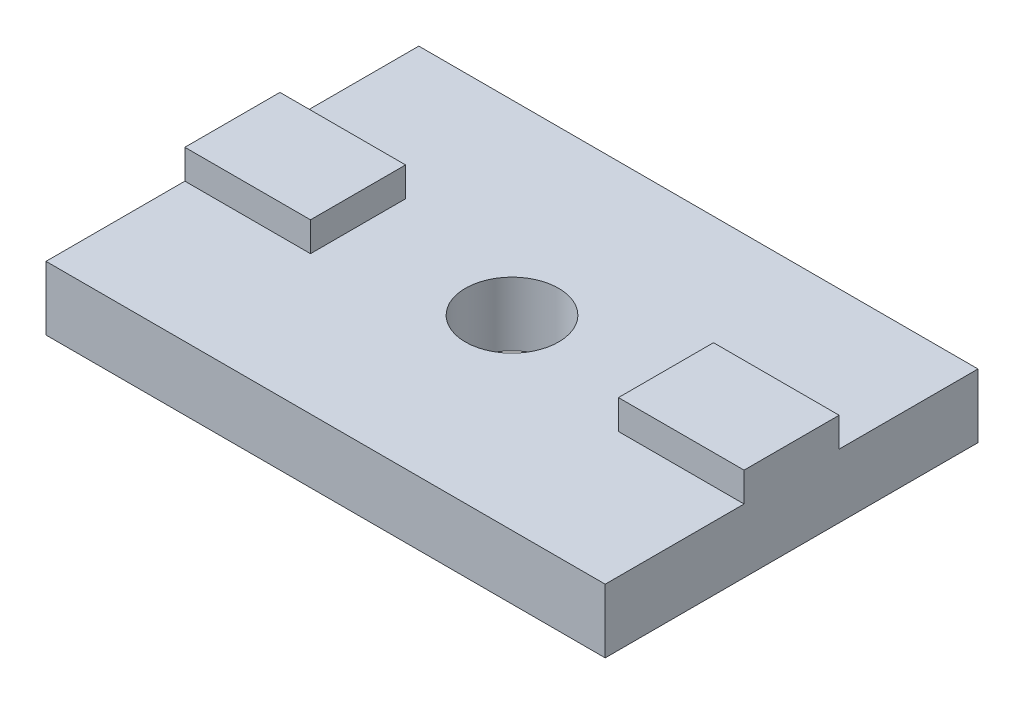
SolidWorks part; units mm, degrees
ref_plane "Front Plane" through (0, 0, 0) normal (0, 0, 1) x (1, 0, 0)
ref_plane "Top Plane" through (0, 0, 0) normal (0, 1, 0) x (1, 0, 0)
ref_plane "Right Plane" through (0, 0, 0) normal (1, 0, 0) x (0, 0, -1)
sketch "Sketch1" plane through (0, 0, 0) normal (0, 1, 0) x (1, 0, 0)
  line L0 (-2.8779, 6.2316) -> (35.2221, 31.6316) construction
  line L1 (-2.8779, 6.2316) -> (35.2221, 6.2316)
  line L2 (-2.8779, 6.2316) -> (-2.8779, 31.6316)
  line L3 (-2.8779, 31.6316) -> (35.2221, 31.6316)
  line L4 (35.2221, 6.2316) -> (35.2221, 31.6316)
  line L5 (35.2221, 31.6316) -> (35.3656, 32.0161) construction
  circle A0 centre (16.1721, 18.9316) radius 3.175
  dimension "D3" = 6.35
  dimension "D1" = 38.1
  dimension "D2" = 25.4
extrude "Boss-Extrude1" add sketch "Sketch1" along normal blind 4.35
sketch "Sketch2" plane through (0, 4.35, 0) normal (0, 1, 0) x (1, 0, 0)
  line L0 (-2.8779, 18.9316) -> (35.2221, 18.9316) construction
  line L1 (-2.8779, 31.6316) -> (-2.8779, 6.2316) construction
  line L2 (35.2221, 6.2316) -> (35.2221, 31.6316) construction
  line L3 (16.1721, 31.6316) -> (16.1721, 6.2316) construction
  line L4 (5.6819, 22.1701) -> (-2.8779, 22.1701)
  line L5 (5.6819, 22.1701) -> (5.6819, 15.6932)
  line L6 (5.6819, 15.6932) -> (-2.8779, 15.6932)
  line L7 (-2.8779, 22.1701) -> (-2.8779, 15.6932)
  line L8 (35.2221, 31.6316) -> (-2.8779, 31.6316) construction
  line L9 (-2.8779, 6.2316) -> (35.2221, 6.2316) construction
  line L10 (26.6623, 22.1701) -> (26.6623, 15.6932)
  line L11 (26.6623, 15.6932) -> (35.2221, 15.6932)
  line L12 (35.2221, 22.1701) -> (35.2221, 15.6932)
  line L13 (26.6623, 22.1701) -> (35.2221, 22.1701)
  line L44 (14.4629, 14.4358) -> (17.8814, 14.4358)
  line L45 (20.1244, 13.5079) -> (23.3518, 10.2864)
  line L46 (22.5885, 8.4414) -> (20.4596, 8.4414)
  line L47 (19.4106, 7.3924) -> (19.4106, 7.2806)
  line L48 (20.4596, 6.2316) -> (21.4892, 6.2316)
  line L49 (22.5052, 6.2316) -> (25.7226, 6.2316)
  line L50 (28.8721, 9.3812) -> (28.8721, 12.5985)
  line L51 (28.8721, 13.6145) -> (28.8721, 14.6442)
  line L52 (27.8231, 15.6932) -> (27.7113, 15.6932)
  line L53 (26.6623, 14.6442) -> (26.6623, 12.5295)
  line L54 (24.9092, 11.8022) -> (21.6131, 15.0908)
  line L55 (20.6806, 17.3384) -> (20.6806, 20.5248)
  line L56 (21.6131, 22.7724) -> (24.9092, 26.061)
  line L57 (26.6623, 25.3337) -> (26.6623, 23.2191)
  line L58 (27.7113, 22.1701) -> (27.8231, 22.1701)
  line L59 (28.8721, 23.2191) -> (28.8721, 24.2487)
  line L60 (28.8721, 25.2647) -> (28.8721, 28.482)
  line L61 (25.7226, 31.6316) -> (22.5052, 31.6316)
  line L62 (21.4892, 31.6316) -> (20.4596, 31.6316)
  line L63 (19.4106, 30.5826) -> (19.4106, 30.4708)
  line L64 (20.4596, 29.4218) -> (22.6489, 29.4218)
  line L65 (23.3792, 27.656) -> (20.0704, 24.3548)
  line L66 (17.8279, 23.4274) -> (14.5163, 23.4274)
  line L67 (12.2738, 24.3548) -> (8.9651, 27.656)
  line L68 (9.6953, 29.4218) -> (11.8846, 29.4218)
  line L69 (12.9336, 30.4708) -> (12.9336, 30.5826)
  line L70 (11.8846, 31.6316) -> (10.855, 31.6316)
  line L71 (9.839, 31.6316) -> (6.6217, 31.6316)
  line L72 (3.4721, 28.482) -> (3.4721, 25.2647)
  line L73 (3.4721, 24.2487) -> (3.4721, 23.2191)
  line L74 (4.5211, 22.1701) -> (4.6329, 22.1701)
  line L75 (5.6819, 23.2191) -> (5.6819, 25.3337)
  line L76 (7.435, 26.061) -> (10.7311, 22.7724)
  line L77 (11.6636, 20.5248) -> (11.6636, 17.3384)
  line L78 (10.7311, 15.0908) -> (7.435, 11.8022)
  line L79 (5.6819, 12.5295) -> (5.6819, 14.6442)
  line L80 (4.6329, 15.6932) -> (4.5211, 15.6932)
  line L81 (3.4721, 14.6442) -> (3.4721, 13.6145)
  line L82 (3.4721, 12.5985) -> (3.4721, 9.3812)
  line L83 (6.6217, 6.2316) -> (9.839, 6.2316)
  line L84 (10.855, 6.2316) -> (11.8846, 6.2316)
  line L85 (12.9336, 7.2806) -> (12.9336, 7.3924)
  line L86 (11.8846, 8.4414) -> (9.7557, 8.4414)
  line L87 (8.9925, 10.2864) -> (12.2198, 13.5079)
  line L88 (14.4629, 14.4358) -> (17.8814, 14.4358) construction
  line L89 (20.1244, 13.5079) -> (23.3518, 10.2864) construction
  line L90 (22.5885, 8.4414) -> (20.4596, 8.4414) construction
  line L91 (19.4106, 7.3924) -> (19.4106, 7.2806) construction
  line L92 (20.4596, 6.2316) -> (21.4892, 6.2316) construction
  line L93 (22.5052, 6.2316) -> (25.7226, 6.2316) construction
  line L94 (28.8721, 9.3812) -> (28.8721, 12.5985) construction
  line L95 (28.8721, 13.6145) -> (28.8721, 14.6442) construction
  line L96 (27.8231, 15.6932) -> (27.7113, 15.6932) construction
  line L97 (26.6623, 14.6442) -> (26.6623, 12.5295) construction
  line L98 (24.9092, 11.8022) -> (21.6131, 15.0908) construction
  line L99 (20.6806, 17.3384) -> (20.6806, 20.5248) construction
  line L100 (21.6131, 22.7724) -> (24.9092, 26.061) construction
  line L101 (26.6623, 25.3337) -> (26.6623, 23.2191) construction
  line L102 (27.7113, 22.1701) -> (27.8231, 22.1701) construction
  line L103 (28.8721, 23.2191) -> (28.8721, 24.2487) construction
  line L104 (28.8721, 25.2647) -> (28.8721, 28.482) construction
  line L105 (25.7226, 31.6316) -> (22.5052, 31.6316) construction
  line L106 (21.4892, 31.6316) -> (20.4596, 31.6316) construction
  line L107 (19.4106, 30.5826) -> (19.4106, 30.4708) construction
  line L108 (20.4596, 29.4218) -> (22.6489, 29.4218) construction
  line L109 (23.3792, 27.656) -> (20.0704, 24.3548) construction
  line L110 (17.8279, 23.4274) -> (14.5163, 23.4274) construction
  line L111 (12.2738, 24.3548) -> (8.9651, 27.656) construction
  line L112 (9.6953, 29.4218) -> (11.8846, 29.4218) construction
  line L113 (12.9336, 30.4708) -> (12.9336, 30.5826) construction
  line L114 (11.8846, 31.6316) -> (10.855, 31.6316) construction
  line L115 (9.839, 31.6316) -> (6.6217, 31.6316) construction
  line L116 (3.4721, 28.482) -> (3.4721, 25.2647) construction
  line L117 (3.4721, 24.2487) -> (3.4721, 23.2191) construction
  line L118 (4.5211, 22.1701) -> (4.6329, 22.1701) construction
  line L119 (5.6819, 23.2191) -> (5.6819, 25.3337) construction
  line L120 (7.435, 26.061) -> (10.7311, 22.7724) construction
  line L121 (11.6636, 20.5248) -> (11.6636, 17.3384) construction
  line L122 (10.7311, 15.0908) -> (7.435, 11.8022) construction
  line L123 (5.6819, 12.5295) -> (5.6819, 14.6442) construction
  line L124 (4.6329, 15.6932) -> (4.5211, 15.6932) construction
  line L125 (3.4721, 14.6442) -> (3.4721, 13.6145) construction
  line L126 (3.4721, 12.5985) -> (3.4721, 9.3812) construction
  line L127 (6.6217, 6.2316) -> (9.839, 6.2316) construction
  line L128 (10.855, 6.2316) -> (11.8846, 6.2316) construction
  line L129 (12.9336, 7.2806) -> (12.9336, 7.3924) construction
  line L130 (11.8846, 8.4414) -> (9.7557, 8.4414) construction
  line L131 (8.9925, 10.2864) -> (12.2198, 13.5079) construction
  arc A52 (20.1244, 13.5079) -> (17.8814, 14.4358) centre (17.8814, 11.2608) ccw
  arc A53 (22.5885, 8.4414) -> (23.3518, 10.2864) centre (22.5885, 9.5218) ccw
  arc A54 (20.4596, 8.4414) -> (19.4106, 7.3924) centre (20.4596, 7.3924) ccw
  arc A55 (19.4106, 7.2806) -> (20.4596, 6.2316) centre (20.4596, 7.2806) ccw
  arc A56 (22.5052, 6.2316) -> (21.4892, 6.2316) centre (21.9972, 6.2316) ccw
  arc A57 (26.7386, 6.2318) -> (25.7226, 6.2316) centre (26.2306, 6.2316) ccw
  arc A58 (26.7386, 6.2318) -> (28.872, 8.3652) centre (26.7639, 8.3398) ccw
  arc A59 (28.8721, 9.3812) -> (28.872, 8.3652) centre (28.8721, 8.8732) ccw
  arc A60 (28.8721, 13.6145) -> (28.8721, 12.5985) centre (28.8721, 13.1065) ccw
  arc A61 (28.8721, 14.6442) -> (27.8231, 15.6932) centre (27.8231, 14.6442) ccw
  arc A62 (27.7113, 15.6932) -> (26.6623, 14.6442) centre (27.7113, 14.6442) ccw
  arc A63 (24.9092, 11.8022) -> (26.6623, 12.5295) centre (25.6349, 12.5295) ccw
  arc A64 (20.6806, 17.3384) -> (21.6131, 15.0908) centre (23.8556, 17.3384) ccw
  arc A65 (21.6131, 22.7724) -> (20.6806, 20.5248) centre (23.8556, 20.5248) ccw
  arc A66 (26.6623, 25.3337) -> (24.9092, 26.061) centre (25.6349, 25.3337) ccw
  arc A67 (26.6623, 23.2191) -> (27.7113, 22.1701) centre (27.7113, 23.2191) ccw
  arc A68 (27.8231, 22.1701) -> (28.8721, 23.2191) centre (27.8231, 23.2191) ccw
  arc A69 (28.8721, 25.2647) -> (28.8721, 24.2487) centre (28.8721, 24.7567) ccw
  arc A70 (28.872, 29.498) -> (28.8721, 28.482) centre (28.8721, 28.99) ccw
  arc A71 (28.872, 29.498) -> (26.7386, 31.6315) centre (26.7639, 29.5234) ccw
  arc A72 (25.7226, 31.6316) -> (26.7386, 31.6315) centre (26.2306, 31.6316) ccw
  arc A73 (21.4892, 31.6316) -> (22.5052, 31.6316) centre (21.9972, 31.6316) ccw
  arc A74 (20.4596, 31.6316) -> (19.4106, 30.5826) centre (20.4596, 30.5826) ccw
  arc A75 (19.4106, 30.4708) -> (20.4596, 29.4218) centre (20.4596, 30.4708) ccw
  arc A76 (23.3792, 27.656) -> (22.6489, 29.4218) centre (22.6489, 28.3879) ccw
  arc A77 (17.8279, 23.4274) -> (20.0704, 24.3548) centre (17.8279, 26.6024) ccw
  arc A78 (12.2738, 24.3548) -> (14.5163, 23.4274) centre (14.5163, 26.6024) ccw
  arc A79 (9.6953, 29.4218) -> (8.9651, 27.656) centre (9.6953, 28.3879) ccw
  arc A80 (11.8846, 29.4218) -> (12.9336, 30.4708) centre (11.8846, 30.4708) ccw
  arc A81 (12.9336, 30.5826) -> (11.8846, 31.6316) centre (11.8846, 30.5826) ccw
  arc A82 (9.839, 31.6316) -> (10.855, 31.6316) centre (10.347, 31.6316) ccw
  arc A83 (5.6057, 31.6315) -> (6.6217, 31.6316) centre (6.1137, 31.6316) ccw
  arc A84 (5.6057, 31.6315) -> (3.4723, 29.498) centre (5.5803, 29.5234) ccw
  arc A85 (3.4721, 28.482) -> (3.4723, 29.498) centre (3.4721, 28.99) ccw
  arc A86 (3.4721, 24.2487) -> (3.4721, 25.2647) centre (3.4721, 24.7567) ccw
  arc A87 (3.4721, 23.2191) -> (4.5211, 22.1701) centre (4.5211, 23.2191) ccw
  arc A88 (4.6329, 22.1701) -> (5.6819, 23.2191) centre (4.6329, 23.2191) ccw
  arc A89 (7.435, 26.061) -> (5.6819, 25.3337) centre (6.7093, 25.3337) ccw
  arc A90 (11.6636, 20.5248) -> (10.7311, 22.7724) centre (8.4886, 20.5248) ccw
  arc A91 (10.7311, 15.0908) -> (11.6636, 17.3384) centre (8.4886, 17.3384) ccw
  arc A92 (5.6819, 12.5295) -> (7.435, 11.8022) centre (6.7093, 12.5295) ccw
  arc A93 (5.6819, 14.6442) -> (4.6329, 15.6932) centre (4.6329, 14.6442) ccw
  arc A94 (4.5211, 15.6932) -> (3.4721, 14.6442) centre (4.5211, 14.6442) ccw
  arc A95 (3.4721, 12.5985) -> (3.4721, 13.6145) centre (3.4721, 13.1065) ccw
  arc A96 (3.4723, 8.3652) -> (3.4721, 9.3812) centre (3.4721, 8.8732) ccw
  arc A97 (3.4723, 8.3652) -> (5.6057, 6.2318) centre (5.5803, 8.3398) ccw
  arc A98 (6.6217, 6.2316) -> (5.6057, 6.2318) centre (6.1137, 6.2316) ccw
  arc A99 (10.855, 6.2316) -> (9.839, 6.2316) centre (10.347, 6.2316) ccw
  arc A100 (11.8846, 6.2316) -> (12.9336, 7.2806) centre (11.8846, 7.2806) ccw
  arc A101 (12.9336, 7.3924) -> (11.8846, 8.4414) centre (11.8846, 7.3924) ccw
  arc A102 (8.9925, 10.2864) -> (9.7557, 8.4414) centre (9.7557, 9.5218) ccw
  arc A103 (14.4629, 14.4358) -> (12.2198, 13.5079) centre (14.4629, 11.2608) ccw
  arc A104 (20.1244, 13.5079) -> (17.8814, 14.4358) centre (17.8814, 11.2608) ccw construction
  arc A105 (22.5885, 8.4414) -> (23.3518, 10.2864) centre (22.5885, 9.5218) ccw construction
  arc A106 (20.4596, 8.4414) -> (19.4106, 7.3924) centre (20.4596, 7.3924) ccw construction
  arc A107 (19.4106, 7.2806) -> (20.4596, 6.2316) centre (20.4596, 7.2806) ccw construction
  arc A108 (22.5052, 6.2316) -> (21.4892, 6.2316) centre (21.9972, 6.2316) ccw construction
  arc A109 (26.7386, 6.2318) -> (25.7226, 6.2316) centre (26.2306, 6.2316) ccw construction
  arc A110 (26.7386, 6.2318) -> (28.872, 8.3652) centre (26.7639, 8.3398) ccw construction
  arc A111 (28.8721, 9.3812) -> (28.872, 8.3652) centre (28.8721, 8.8732) ccw construction
  arc A112 (28.8721, 13.6145) -> (28.8721, 12.5985) centre (28.8721, 13.1065) ccw construction
  arc A113 (28.8721, 14.6442) -> (27.8231, 15.6932) centre (27.8231, 14.6442) ccw construction
  arc A114 (27.7113, 15.6932) -> (26.6623, 14.6442) centre (27.7113, 14.6442) ccw construction
  arc A115 (24.9092, 11.8022) -> (26.6623, 12.5295) centre (25.6349, 12.5295) ccw construction
  arc A116 (20.6806, 17.3384) -> (21.6131, 15.0908) centre (23.8556, 17.3384) ccw construction
  arc A117 (21.6131, 22.7724) -> (20.6806, 20.5248) centre (23.8556, 20.5248) ccw construction
  arc A118 (26.6623, 25.3337) -> (24.9092, 26.061) centre (25.6349, 25.3337) ccw construction
  arc A119 (26.6623, 23.2191) -> (27.7113, 22.1701) centre (27.7113, 23.2191) ccw construction
  arc A120 (27.8231, 22.1701) -> (28.8721, 23.2191) centre (27.8231, 23.2191) ccw construction
  arc A121 (28.8721, 25.2647) -> (28.8721, 24.2487) centre (28.8721, 24.7567) ccw construction
  arc A122 (28.872, 29.498) -> (28.8721, 28.482) centre (28.8721, 28.99) ccw construction
  arc A123 (28.872, 29.498) -> (26.7386, 31.6315) centre (26.7639, 29.5234) ccw construction
  arc A124 (25.7226, 31.6316) -> (26.7386, 31.6315) centre (26.2306, 31.6316) ccw construction
  arc A125 (21.4892, 31.6316) -> (22.5052, 31.6316) centre (21.9972, 31.6316) ccw construction
  arc A126 (20.4596, 31.6316) -> (19.4106, 30.5826) centre (20.4596, 30.5826) ccw construction
  arc A127 (19.4106, 30.4708) -> (20.4596, 29.4218) centre (20.4596, 30.4708) ccw construction
  arc A128 (23.3792, 27.656) -> (22.6489, 29.4218) centre (22.6489, 28.3879) ccw construction
  arc A129 (17.8279, 23.4274) -> (20.0704, 24.3548) centre (17.8279, 26.6024) ccw construction
  arc A130 (12.2738, 24.3548) -> (14.5163, 23.4274) centre (14.5163, 26.6024) ccw construction
  arc A131 (9.6953, 29.4218) -> (8.9651, 27.656) centre (9.6953, 28.3879) ccw construction
  arc A132 (11.8846, 29.4218) -> (12.9336, 30.4708) centre (11.8846, 30.4708) ccw construction
  arc A133 (12.9336, 30.5826) -> (11.8846, 31.6316) centre (11.8846, 30.5826) ccw construction
  arc A134 (9.839, 31.6316) -> (10.855, 31.6316) centre (10.347, 31.6316) ccw construction
  arc A135 (5.6057, 31.6315) -> (6.6217, 31.6316) centre (6.1137, 31.6316) ccw construction
  arc A136 (5.6057, 31.6315) -> (3.4723, 29.498) centre (5.5803, 29.5234) ccw construction
  arc A137 (3.4721, 28.482) -> (3.4723, 29.498) centre (3.4721, 28.99) ccw construction
  arc A138 (3.4721, 24.2487) -> (3.4721, 25.2647) centre (3.4721, 24.7567) ccw construction
  arc A139 (3.4721, 23.2191) -> (4.5211, 22.1701) centre (4.5211, 23.2191) ccw construction
  arc A140 (4.6329, 22.1701) -> (5.6819, 23.2191) centre (4.6329, 23.2191) ccw construction
  arc A141 (7.435, 26.061) -> (5.6819, 25.3337) centre (6.7093, 25.3337) ccw construction
  arc A142 (11.6636, 20.5248) -> (10.7311, 22.7724) centre (8.4886, 20.5248) ccw construction
  arc A143 (10.7311, 15.0908) -> (11.6636, 17.3384) centre (8.4886, 17.3384) ccw construction
  arc A144 (5.6819, 12.5295) -> (7.435, 11.8022) centre (6.7093, 12.5295) ccw construction
  arc A145 (5.6819, 14.6442) -> (4.6329, 15.6932) centre (4.6329, 14.6442) ccw construction
  arc A146 (4.5211, 15.6932) -> (3.4721, 14.6442) centre (4.5211, 14.6442) ccw construction
  arc A147 (3.4721, 12.5985) -> (3.4721, 13.6145) centre (3.4721, 13.1065) ccw construction
  arc A148 (3.4723, 8.3652) -> (3.4721, 9.3812) centre (3.4721, 8.8732) ccw construction
  arc A149 (3.4723, 8.3652) -> (5.6057, 6.2318) centre (5.5803, 8.3398) ccw construction
  arc A150 (6.6217, 6.2316) -> (5.6057, 6.2318) centre (6.1137, 6.2316) ccw construction
  arc A151 (10.855, 6.2316) -> (9.839, 6.2316) centre (10.347, 6.2316) ccw construction
  arc A152 (11.8846, 6.2316) -> (12.9336, 7.2806) centre (11.8846, 7.2806) ccw construction
  arc A153 (12.9336, 7.3924) -> (11.8846, 8.4414) centre (11.8846, 7.3924) ccw construction
  arc A154 (8.9925, 10.2864) -> (9.7557, 8.4414) centre (9.7557, 9.5218) ccw construction
  arc A155 (14.4629, 14.4358) -> (12.2198, 13.5079) centre (14.4629, 11.2608) ccw construction
  dimension "D1" = 0
extrude "Boss-Extrude2" add sketch "Sketch2" along normal blind 2
